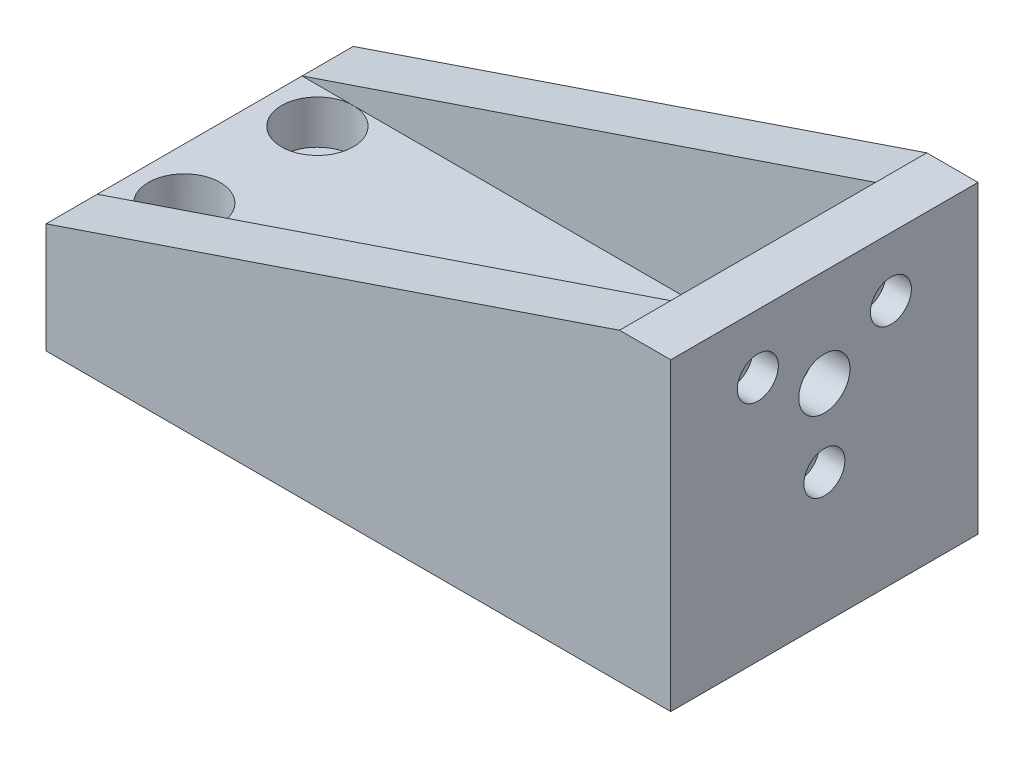
SolidWorks part; units mm, degrees
ref_plane "Front Plane" through (0, 0, 0) normal (0, 0, 1) x (1, 0, 0)
ref_plane "Top Plane" through (0, 0, 0) normal (0, 1, 0) x (1, 0, 0)
ref_plane "Right Plane" through (0, 0, 0) normal (1, 0, 0) x (0, 0, -1)
sketch "Sketch5" plane through (0, 0, 0) normal (1, 0, 0) x (0, 0, -1)
  line L0 (0, 0) -> (0, 50000) construction
  line L1 (-15, -20.25) -> (15, -20.25)
  line L2 (-15, -20.25) -> (-15, 9.5)
  line L3 (-15, 9.5) -> (15, 9.5)
  line L4 (15, -20.25) -> (15, 9.5)
  line L5 (0, 0) -> (43301.2702, 25000) construction
  line L7 (0, 0) -> (50000, 0) construction
  circle A0 centre (0, 0) radius 2.5
  circle A1 centre (0, 0) radius 9.5 construction
  circle A2 centre (6.4952, 3.75) radius 1
  circle A3 centre (0, -7.5) radius 1
  circle A4 centre (-6.4952, 3.75) radius 1
  point P23 (0, 0)
  dimension "D3" = 5
  dimension "D4" = 19
  dimension "D6" = 2
  dimension "D7" = 1
  dimension "D1" = 20.25
  dimension "D2" = 30
  dimension "D5" = 60
  dimension "D8" = 3
extrude "Boss-Extrude3" add sketch "Sketch5" against normal blind 5
sketch "Sketch10" plane through (0, 0, 0) normal (1, 0, 0) x (0, 0, -1)
  circle A0 centre (-6.4952, 3.75) radius 2
  circle A1 centre (6.4952, 3.75) radius 2
  circle A2 centre (0, -7.5) radius 2
  dimension "D1" = 4
extrude "Cut-Extrude8" cut sketch "Sketch10" against normal blind 2.5
sketch "Sketch11" plane through (-5, 0, 0) normal (-1, 0, 0) x (0, 0, 1)
  line L0 (15, 9.5) -> (15, -20.25) construction
  line L1 (-15, -20.25) -> (15, -20.25)
  line L2 (-15, -20.25) -> (-15, -9.5)
  line L3 (-15, -9.5) -> (15, -9.5)
  line L4 (15, -20.25) -> (15, -9.5)
  circle A0 centre (0, 0) radius 9.5 construction
  dimension "D2" = 19
extrude "Boss-Extrude4" add sketch "Sketch11" along normal blind 56
ref_plane "Plane1" through (0, 0, -15) normal (0, 0, -1) x (-1, 0, 0)
sketch "Sketch12" plane through (0, 0, -15) normal (0, 0, -1) x (-1, 0, 0)
  line L0 (5, -9.5) -> (61, -9.5)
  line L1 (61, -9.5) -> (5, 9.5)
  line L2 (5, 9.5) -> (5, -9.5)
extrude "Boss-Extrude5" add sketch "Sketch12" against normal blind 5
mirror "Mirror1" about plane through (0, 0, 0) normal (0, 0, 1) of "Boss-Extrude5"
sketch "Sketch13" plane through (-5, 0, 0) normal (-1, 0, 0) x (0, 0, 1)
  circle A0 centre (0, 0) radius 6.25
  dimension "D1" = 12.5
extrude "Cut-Extrude9" cut sketch "Sketch13" against normal blind 1.5
sketch "Sketch16" plane through (0, -9.5, 0) normal (0, 1, 0) x (1, 0, 0)
  line L0 (-61, 0) -> (0, 0) construction
  line L1 (-61, -10) -> (-61, 10) construction
  line L2 (-30.5, 0) -> (-30.5, 15) construction
  line L3 (16.3625, 15) -> (-16.3625, 15) construction
  line L4 (-30.5, 0) -> (-30.5, -15) construction
  line L5 (-61, -15) -> (-5, -15) construction
  line L6 (0, 15) -> (0, -15) construction
  line L17 (-61, 10) -> (-5, 10) construction
  circle A0 centre (-11, 6.5) radius 3.5
  circle A1 centre (-56, 6.5) radius 3.5
  circle A2 centre (-56, -6.5) radius 3.5
  circle A3 centre (-11, -6.5) radius 3.5
  point P24 (0, 0)
  point P25 (0, 0)
  dimension "D3" = 7
  dimension "D1" = 2
  dimension "D2" = 11
extrude "Cut-Extrude10" cut sketch "Sketch16" against normal blind 4.25
sketch "Sketch17" plane through (0, -13.75, 0) normal (0, 1, 0) x (1, 0, 0)
  line L0 (-59.5, 6.5) -> (-52.5, 6.5) construction
  line L1 (-56, 3) -> (-56, 10) construction
  circle A4 centre (-56, 6.5) radius 3.5 construction
  circle A5 centre (-56, 6.5) radius 3.5 construction
  circle A6 centre (-56, 6.5) radius 2
  circle A7 centre (-11, 6.5) radius 2
  circle A8 centre (-11, -6.5) radius 2
  circle A9 centre (-56, -6.5) radius 2
  dimension "D1" = 4
  dimension "D2" = 2
  dimension "D3" = 2
extrude "Cut-Extrude11" cut sketch "Sketch17" against normal up to surface (6.5 mm away) up to face at (-30.5, -20.25, 0)
